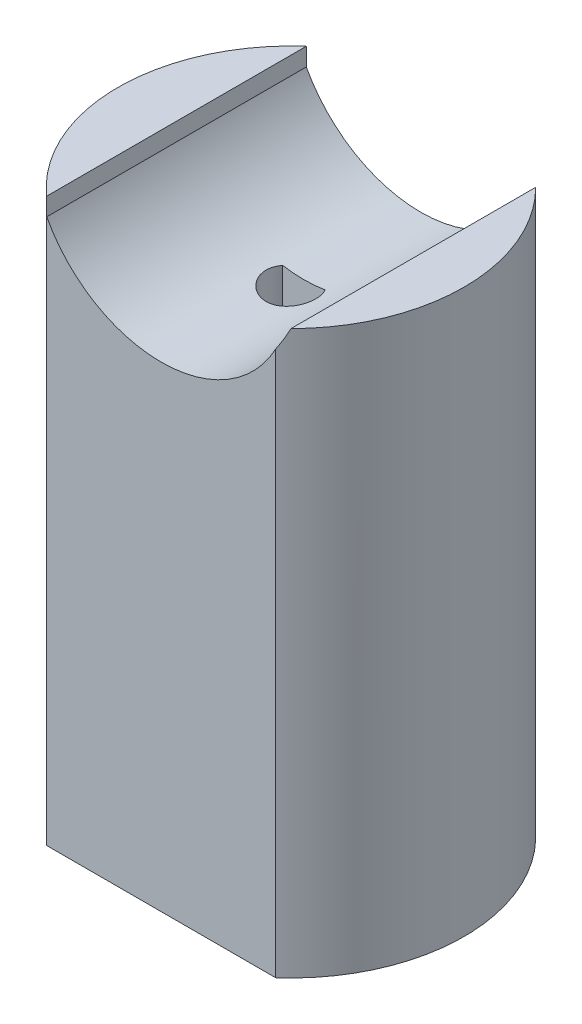
SolidWorks part; units mm, degrees
ref_plane "Front Plane" through (0, 0, 0) normal (0, 0, 1) x (1, 0, 0)
ref_plane "Top Plane" through (0, 0, 0) normal (0, 1, 0) x (1, 0, 0)
ref_plane "Right Plane" through (0, 0, 0) normal (1, 0, 0) x (0, 0, -1)
sketch "Sketch1" plane through (0, 0, 0) normal (0, 1, 0) x (1, 0, 0)
  line L0 (-2.4527, 1.5) -> (2.4527, 1.5)
  circle A0 centre (0, 0) radius 2.875
  circle A1 centre (0, 0) radius 20
  dimension "D1" = 5.75
  dimension "D3" = 40
  dimension "D2" = 1.5
extrude "Boss-Extrude1" add sketch "Sketch1" along normal blind 30 contours A1 A0 | L0 A0
ref_plane "Plane1" through (0, 0, -20) normal (0, 0, -1) x (-1, 0, 0)
sketch "Sketch2" plane through (0, 0, -20) normal (0, 0, -1) x (-1, 0, 0)
  line L0 (-20, 0) -> (20, 0) construction
  circle A0 centre (0, 15) radius 1.5
  point P0 (0, 15)
  dimension "D2" = 3
  dimension "D1" = 15
extrude "Cut-Extrude1" cut sketch "Sketch2" against normal up to surface (18.5 mm away) up to face at (0, 15, -1.5)
sketch "Sketch3" plane through (0, 30, 0) normal (0, 1, 0) x (1, 0, 0)
  line L1 (28.5412, 15) -> (-28.5412, 15)
  line L2 (28.5412, 15) -> (28.5412, -15)
  line L3 (28.5412, -15) -> (-28.5412, -15)
  line L4 (-28.5412, 15) -> (-28.5412, -15)
  line L5 (28.5412, 15) -> (-28.5412, -15) construction
  line L6 (28.5412, -15) -> (-28.5412, 15) construction
  circle A0 centre (0, 0) radius 20
  point P0 (0, 0)
  circle M6 centre (0, 0) radius 20
  dimension "D1" = 30
extrude "Cut-Extrude2" cut sketch "Sketch3" against normal through all contours L3 M6 | L1 M6
sketch "Sketch4" plane through (0, 30, 0) normal (0, 1, 0) x (1, 0, 0)
  line L0 (-2.4527, 1.5) -> (2.4527, 1.5) construction
  line L1 (-2.4527, 1.5) -> (2.4527, 1.5)
  line L2 (-13.2288, -15) -> (13.2288, -15)
  line L3 (13.2288, 15) -> (-13.2288, 15)
  line L4 (-13.2288, -15) -> (13.2288, -15)
  line L5 (13.2288, 15) -> (-13.2288, 15)
  arc A0 (-2.4527, 1.5) -> (2.4527, 1.5) centre (0, 0) ccw construction
  arc A1 (-2.4527, 1.5) -> (2.4527, 1.5) centre (0, 0) ccw
  arc A2 (13.2288, -15) -> (13.2288, 15) centre (0, 0) ccw
  arc A3 (-13.2288, 15) -> (-13.2288, -15) centre (0, 0) ccw
  arc A4 (13.2288, -15) -> (13.2288, 15) centre (0, 0) ccw
  arc A5 (-13.2288, 15) -> (-13.2288, -15) centre (0, 0) ccw
  dimension "D1" = 0
extrude "Boss-Extrude2" add sketch "Sketch4" along normal blind 40
sketch "Sketch5" plane through (0, 0, 15) normal (0, 0, 1) x (1, 0, 0)
  line L0 (-13.2288, 70) -> (13.2288, 70) construction
  line L1 (20, 0) -> (20, 70) construction
  line L2 (-20, 75) -> (20, 75)
  line L3 (-20, 75) -> (-20, 65)
  line L4 (-20, 65) -> (20, 65)
  line L5 (20, 75) -> (20, 65)
  line L6 (-20, 75) -> (20, 65) construction
  line L7 (-20, 65) -> (20, 75) construction
  circle A0 centre (0, 70) radius 15
  line M2 (13.2288, 0) -> (13.2288, 70)
  line M3 (13.2288, 70) -> (-13.2288, 70)
  line M4 (-13.2288, 70) -> (-13.2288, 0)
  dimension "D1" = 30
  dimension "D2" = 10
extrude "Cut-Extrude3" cut sketch "Sketch5" against normal through all contours L4 M4 M2 M3 | A0 L4 M4 M2 | L2 A0 L4 M4 M3 M2 | A0 L4 L5 L2 | A0 L4 M2 | A0 L2 L3 L4
